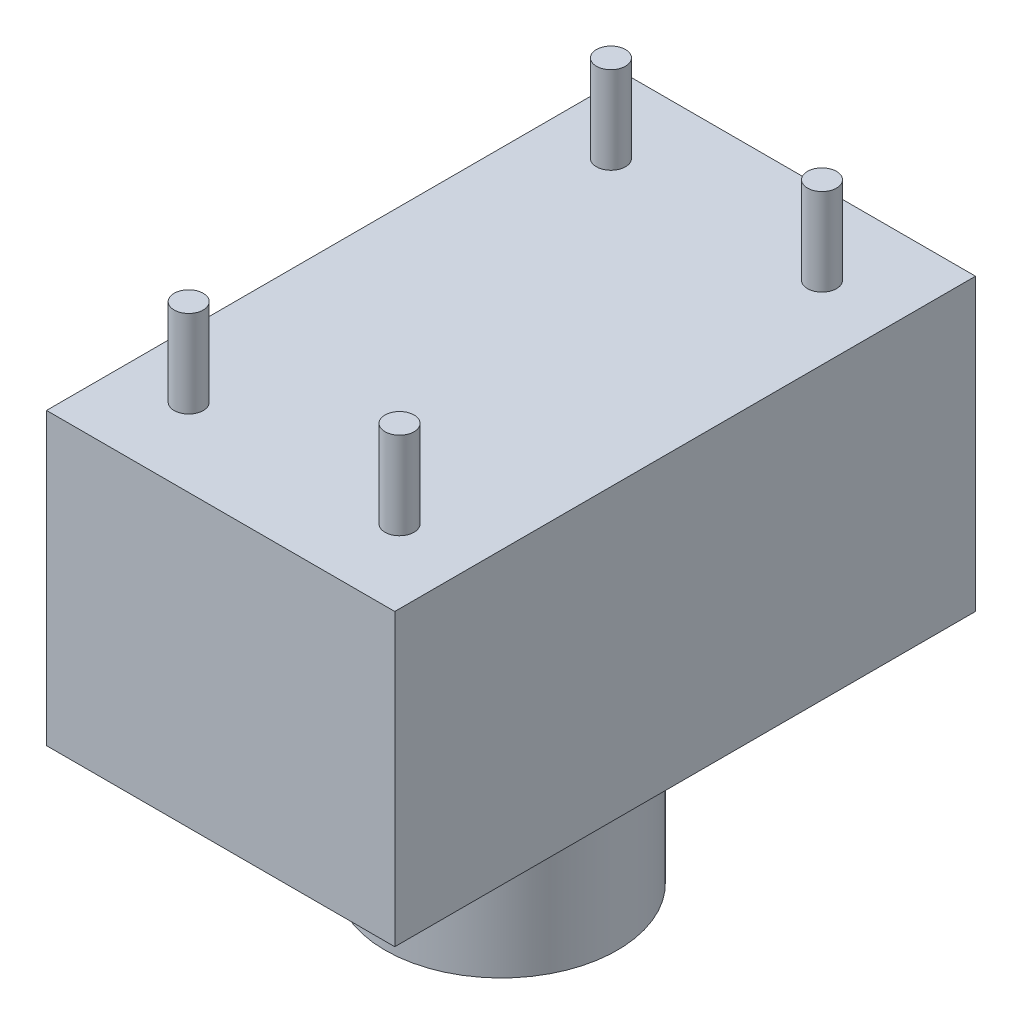
SolidWorks part; units mm, degrees
material "AISI 304"
ref_plane "Front Plane" through (0, 0, 0) normal (0, 0, 1) x (1, 0, 0)
ref_plane "Top Plane" through (0, 0, 0) normal (0, 1, 0) x (1, 0, 0)
ref_plane "Right Plane" through (0, 0, 0) normal (1, 0, 0) x (0, 0, -1)
sketch "Sketch2" plane through (0, 0, -0.1455) normal (0, 1, 0) x (1, 0, 0)
  line L1 (-92.2157, 37.8406) -> (-80.2223, 37.8406)
  line L2 (-92.2157, 37.8406) -> (-92.2157, 17.8406)
  line L3 (-92.2157, 17.8406) -> (-80.2223, 17.8406)
  line L4 (-80.2223, 37.8406) -> (-80.2223, 17.8406)
extrude "Boss-Extrude1" add sketch "Sketch2" along normal blind 10 and the other way blind 0.0001 contours L1 L4 L3 L2
sketch "Sketch3" plane through (-2.2852, 0, 0) normal (0, 1, 0) x (1, 0, 0)
  circle A0 centre (-83.9992, 27.7143) radius 4
extrude "Boss-Extrude3" add sketch "Sketch3" against normal blind 6 contours A0
sketch "Sketch4" plane through (-0.4196, 10, -0.1455) normal (0, 1, 0) x (1, 0, 0)
  circle A0 centre (-89.5921, 35.0752) radius 0.5
  circle A1 centre (-82.3226, 35.0752) radius 0.5
  circle A2 centre (-82.3317, 20.5337) radius 0.5
  circle A3 centre (-89.5921, 20.5337) radius 0.5
extrude "Boss-Extrude4" add sketch "Sketch4" along normal blind 3
